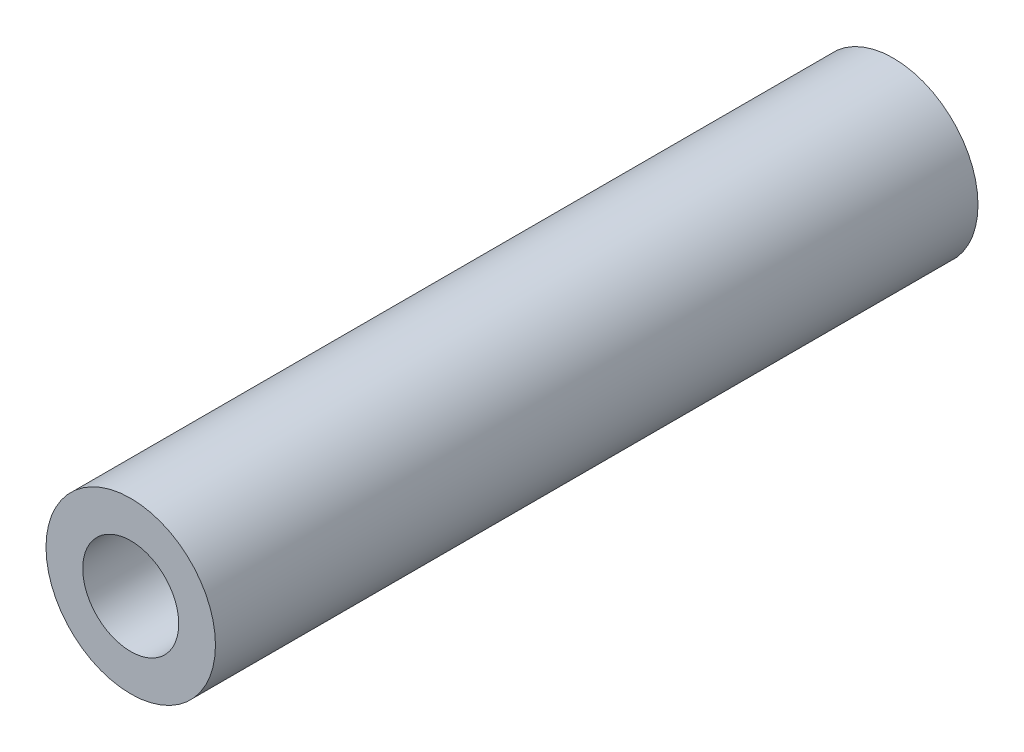
SolidWorks part; units mm, degrees
ref_plane "Front Plane" through (0, 0, 0) normal (0, 0, 1) x (1, 0, 0)
ref_plane "Top Plane" through (0, 0, 0) normal (0, 1, 0) x (1, 0, 0)
ref_plane "Right Plane" through (0, 0, 0) normal (1, 0, 0) x (0, 0, -1)
sketch "Sketch1" plane through (0, 0, 0) normal (0, 0, 1) x (1, 0, 0)
  circle A0 centre (0, 0) radius 3
  circle A1 centre (0, 0) radius 1.7
extrude "Ring_Envelope" add sketch "Sketch1" along normal blind 27
